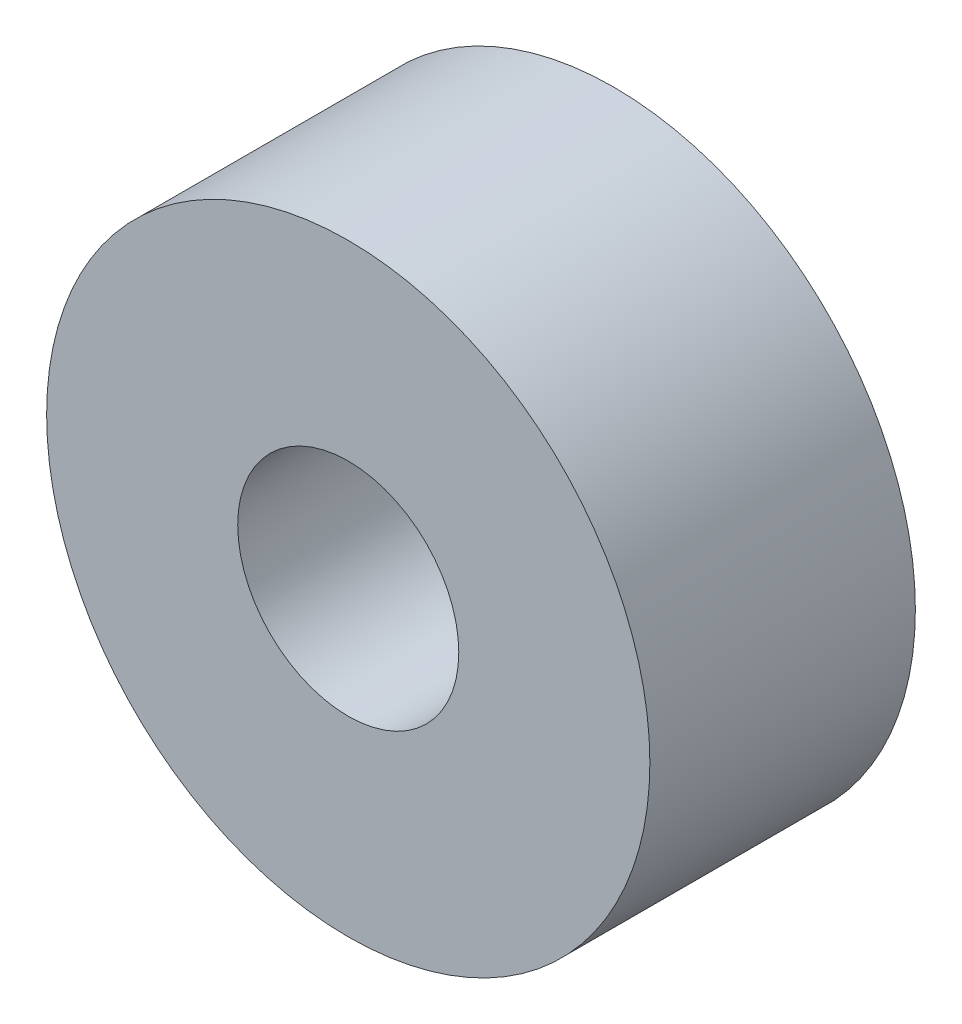
SolidWorks part; units mm, degrees
ref_plane "Front Plane" through (0, 0, 0) normal (0, 0, 1) x (1, 0, 0)
ref_plane "Top Plane" through (0, 0, 0) normal (0, 1, 0) x (1, 0, 0)
ref_plane "Right Plane" through (0, 0, 0) normal (1, 0, 0) x (0, 0, -1)
sketch "Sketch1" plane through (0, 0, 0) normal (0, 0, 1) x (1, 0, 0)
  circle A0 centre (0, 0) radius 8.35
  dimension "D1" = 16.7
extrude "Boss-Extrude1" add sketch "Sketch1" along normal blind 7.35
sketch "Sketch2" plane through (0, 0, 7.35) normal (0, 0, 1) x (1, 0, 0)
  circle A0 centre (0, 0) radius 3.06
  dimension "D1" = 6.12
extrude "Cut-Extrude1" cut sketch "Sketch2" against normal through all
